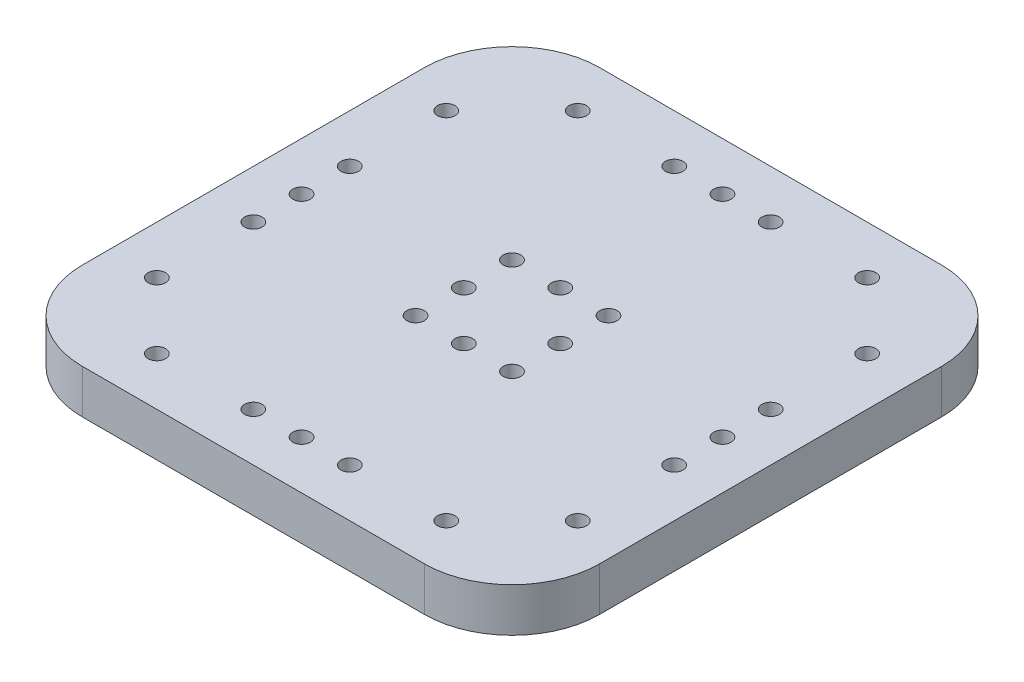
SolidWorks part; units mm, degrees
ref_plane "Front Plane" through (0, 0, 0) normal (0, 0, 1) x (1, 0, 0)
ref_plane "Top Plane" through (0, 0, 0) normal (0, 1, 0) x (1, 0, 0)
ref_plane "Right Plane" through (0, 0, 0) normal (1, 0, 0) x (0, 0, -1)
sketch "Sketch1" plane through (0, 0, 0) normal (0, 1, 0) x (1, 0, 0)
  line L0 (-1.371, 1.1217) -> (-1.371, -46.8783) construction
  line L1 (-12.371, -46.8783) -> (9.629, -46.8783) construction
  line L2 (9.629, -46.8783) -> (31.629, -46.8783) construction
  line L3 (-12.371, -46.8783) -> (-34.371, -46.8783) construction
  line L4 (-1.371, 1.1217) -> (-1.371, -9.8783) construction
  line L5 (-12.371, -9.8783) -> (9.629, -9.8783) construction
  line L6 (-1.371, 1.1217) -> (-12.371, 1.1217) construction
  line L7 (-12.371, 49.1217) -> (-34.371, 49.1217) construction
  line L8 (9.629, 49.1217) -> (31.629, 49.1217) construction
  line L9 (-12.371, 49.1217) -> (9.629, 49.1217) construction
  line L10 (-60.371, 60.1217) -> (57.629, -57.8783) construction
  line L11 (46.629, 12.1217) -> (46.629, 34.1217) construction
  line L12 (46.629, -9.8783) -> (46.629, -31.8783) construction
  line L13 (46.629, 12.1217) -> (46.629, -9.8783) construction
  line L14 (-49.371, 12.1217) -> (-49.371, -9.8783) construction
  line L15 (-49.371, -9.8783) -> (-49.371, -31.8783) construction
  line L16 (-49.371, 12.1217) -> (-49.371, 34.1217) construction
  line L18 (-60.371, 60.1217) -> (57.629, 60.1217)
  line L19 (-60.371, 60.1217) -> (-60.371, -57.8783)
  line L20 (-60.371, -57.8783) -> (57.629, -57.8783)
  line L21 (57.629, 60.1217) -> (57.629, -57.8783)
  line L22 (-60.371, 60.1217) -> (57.629, -57.8783) construction
  line L23 (-60.371, -57.8783) -> (57.629, 60.1217) construction
  circle A0 centre (-1.371, -46.8783) radius 2
  circle A1 centre (9.629, -46.8783) radius 2
  circle A2 centre (31.629, -46.8783) radius 2
  circle A3 centre (-34.371, -46.8783) radius 2
  circle A4 centre (-12.371, -46.8783) radius 2
  circle A5 centre (-1.371, -9.8783) radius 2
  circle A6 centre (9.629, -9.8783) radius 2
  circle A7 centre (-12.371, -9.8783) radius 2
  circle A8 centre (-12.371, 1.1217) radius 2
  circle A9 centre (-12.371, 12.1217) radius 2
  circle A10 centre (9.629, 12.1217) radius 2
  circle A11 centre (-1.371, 12.1217) radius 2
  circle A12 centre (-12.371, 49.1217) radius 2
  circle A13 centre (-34.371, 49.1217) radius 2
  circle A14 centre (31.629, 49.1217) radius 2
  circle A15 centre (9.629, 49.1217) radius 2
  circle A16 centre (-1.371, 49.1217) radius 2
  circle A17 centre (9.629, 1.1217) radius 2
  circle A18 centre (46.629, 12.1217) radius 2
  circle A19 centre (46.629, 34.1217) radius 2
  circle A20 centre (46.629, -31.8783) radius 2
  circle A21 centre (46.629, -9.8783) radius 2
  circle A22 centre (46.629, 1.1217) radius 2
  circle A23 centre (-49.371, 1.1217) radius 2
  circle A24 centre (-49.371, -9.8783) radius 2
  circle A25 centre (-49.371, -31.8783) radius 2
  circle A26 centre (-49.371, 34.1217) radius 2
  circle A27 centre (-49.371, 12.1217) radius 2
  dimension "D1" = 48
  dimension "D2" = 11
  dimension "D3" = 22
  dimension "D4" = 11
extrude "Boss-Extrude1" add sketch "Sketch1" along normal blind 10
fillet "Fillet1" radius 20 4 edges at (-60.371, 5, -60.1217) (57.629, 5, -60.1217) (57.629, 5, 57.8783) (-60.371, 5, 57.8783)
ref_plane "Plane1" through (0, 0, -1.1217) normal (0, 0, 1) x (1, 0, 0)
ref_plane "Plane2" through (-1.371, 0, 0) normal (1, 0, 0) x (0, 0, -1)
